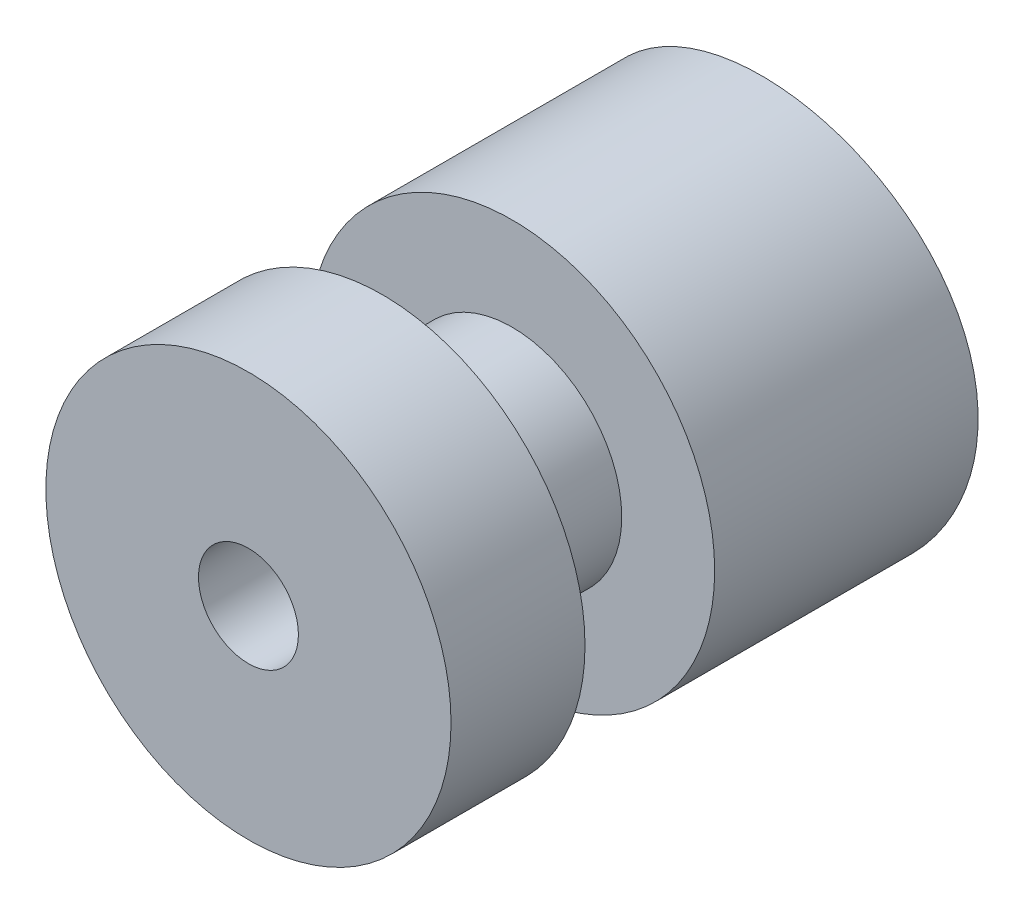
SolidWorks part; units mm, degrees
material "Nylon 6/10"
ref_plane "Front Plane" through (0, 0, 0) normal (0, 0, 1) x (1, 0, 0)
ref_plane "Top Plane" through (0, 0, 0) normal (0, 1, 0) x (1, 0, 0)
ref_plane "Right Plane" through (0, 0, 0) normal (1, 0, 0) x (0, 0, -1)
sketch "Sketch1" plane through (0, 0, 0) normal (0, 0, 1) x (1, 0, 0)
  circle A0 centre (0, 0) radius 9.525
  circle A1 centre (0, 0) radius 2.3495
extrude "Extrude1" add sketch "Sketch1" along normal blind 24.7828
ref_plane "Plane1" through (0, 0, 18.4836) normal (0, 0, 1) x (1, 0, 0)
sketch "Sketch2" plane through (0, 0, 18.4836) normal (0, 0, 1) x (1, 0, 0)
  circle A0 centre (0, 0) radius 5.1562
extrude "Extrude2" cut sketch "Sketch2" against normal blind 6.096 flip side to cut
sketch "Sketch3" plane through (0, 0, 0) normal (0, 1, 0) x (1, 0, 0)
  arc A0 (9.525, 0) -> (-9.525, 0) centre (0, 69.1975) cw
extrude "Extrude3" cut sketch "Sketch3" against normal through all and the other way through all flip side to cut
